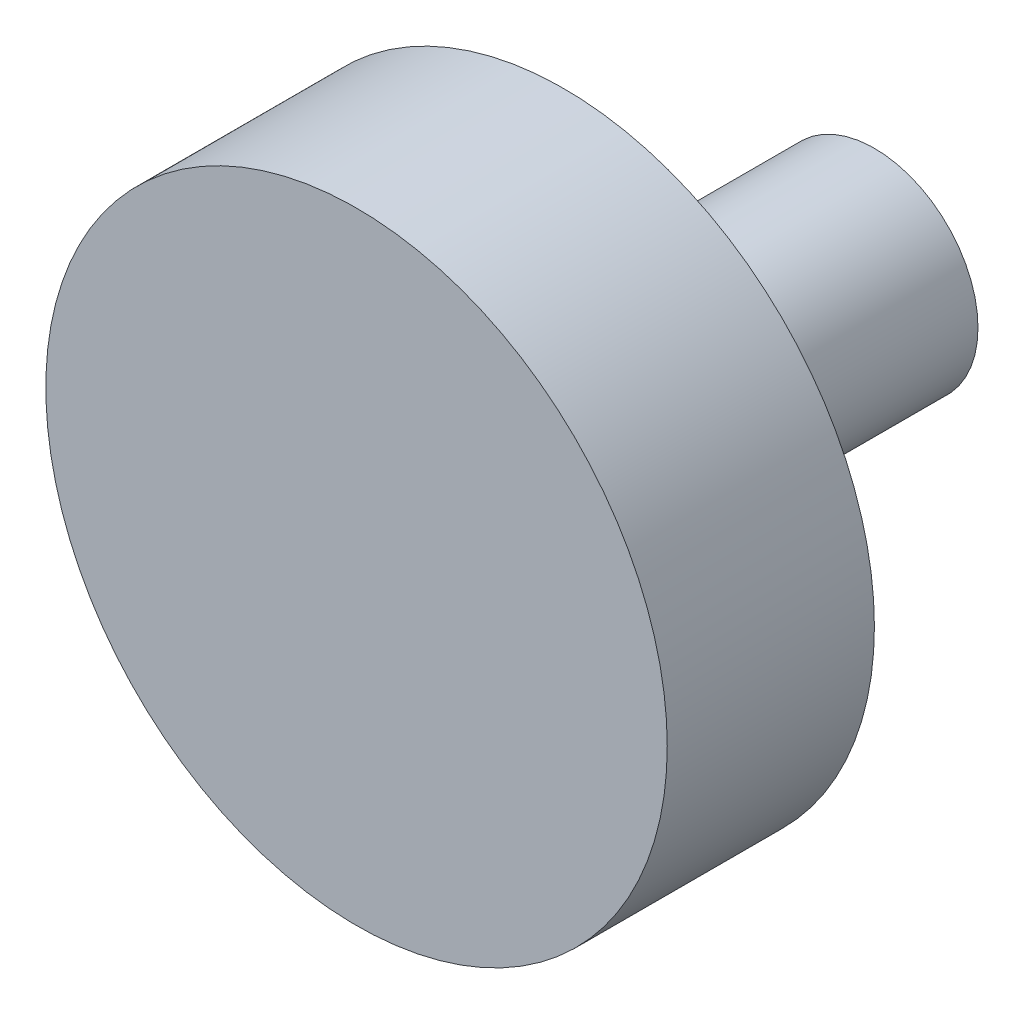
SolidWorks part; units mm, degrees
ref_plane "Front Plane" through (0, 0, 0) normal (0, 0, 1) x (1, 0, 0)
ref_plane "Top Plane" through (0, 0, 0) normal (0, 1, 0) x (1, 0, 0)
ref_plane "Right Plane" through (0, 0, 0) normal (1, 0, 0) x (0, 0, -1)
sketch "Sketch1" plane through (0, 0, 0) normal (0, 0, 1) x (1, 0, 0)
  circle A0 centre (0, 0) radius 2.5
  dimension "D1" = 5
extrude "Boss-Extrude1" add sketch "Sketch1" along normal blind 7.5
sketch "Sketch2" plane through (0, 0, 7.5) normal (0, 0, 1) x (1, 0, 0)
  circle A0 centre (0, 0) radius 7.5
  dimension "D1" = 15
extrude "Boss-Extrude4" add sketch "Sketch2" along normal blind 5
